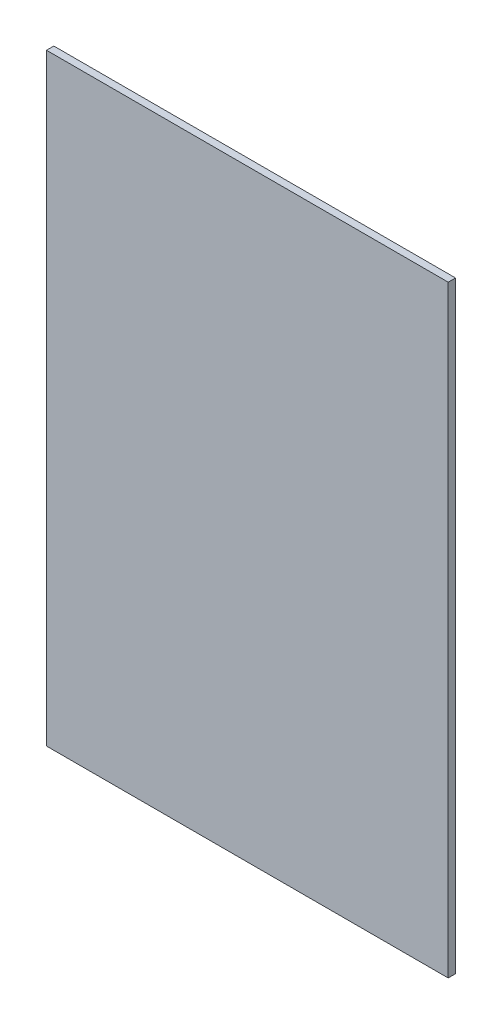
SolidWorks part; units mm, degrees
material "OSB_Plywood"
ref_plane "Front Plane" through (0, 0, 0) normal (0, 0, 1) x (1, 0, 0)
ref_plane "Top Plane" through (0, 0, 0) normal (0, 1, 0) x (1, 0, 0)
ref_plane "Right Plane" through (0, 0, 0) normal (1, 0, 0) x (0, 0, -1)
sketch "Sketch1" plane through (0, 0, 0) normal (0, 0, 1) x (1, 0, 0)
  line L1 (0, 0) -> (609.6, 0)
  line L2 (0, 0) -> (0, 914.4)
  line L3 (0, 914.4) -> (609.6, 914.4)
  line L4 (609.6, 0) -> (609.6, 914.4)
  dimension "D1" = 609.6
  dimension "D2" = 914.4
extrude "Boss-Extrude1" add sketch "Sketch1" along normal blind 11.1125
